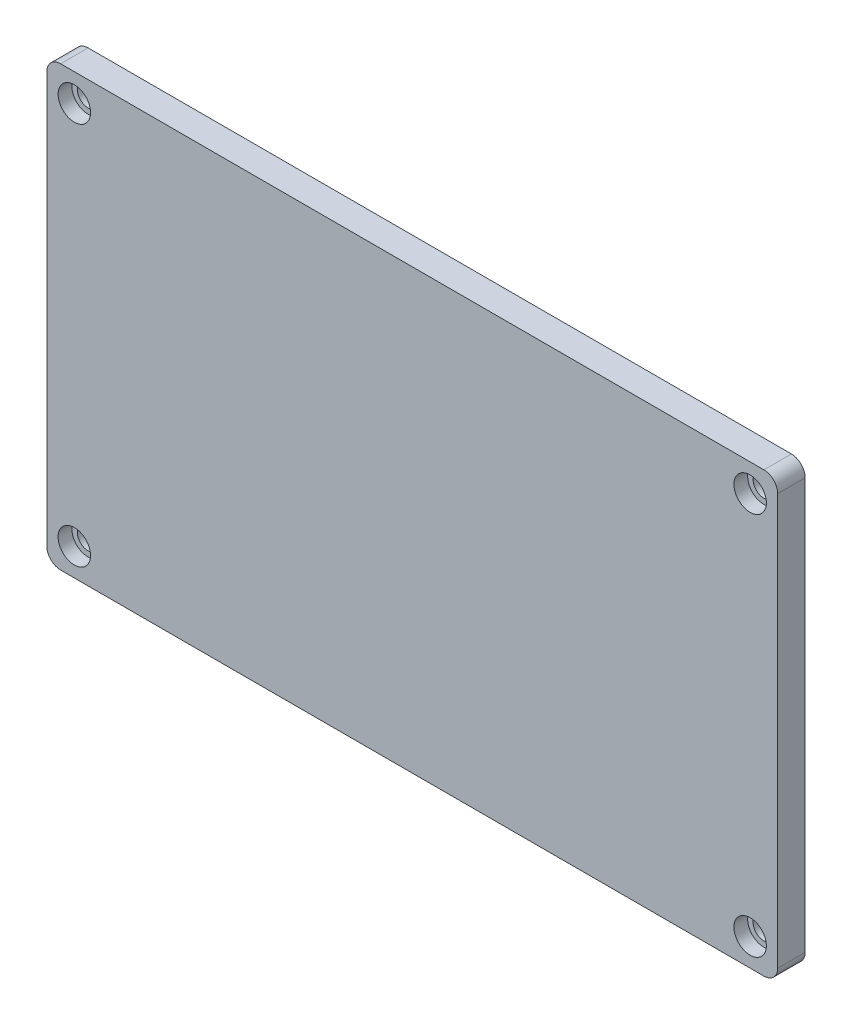
SolidWorks part; units mm, degrees
ref_plane "Front Plane" through (0, 0, 0) normal (0, 0, 1) x (1, 0, 0)
ref_plane "Top Plane" through (0, 0, 0) normal (0, 1, 0) x (1, 0, 0)
ref_plane "Right Plane" through (0, 0, 0) normal (1, 0, 0) x (0, 0, -1)
sketch "Sketch1" plane through (0, 0, 0) normal (0, 0, 1) x (1, 0, 0)
  line L15 (-71.9016, 23.565) -> (-69.4016, 23.565)
  line L16 (-71.9016, 23.565) -> (-71.9016, 20.771)
  line L17 (-71.9016, 20.771) -> (-69.4016, 20.771)
  line L18 (-69.4016, 23.565) -> (-69.4016, 20.771)
  line L26 (-69.3616, -8.232) -> (60.5584, -8.232)
  line L27 (63.0984, -5.692) -> (63.0984, 70.228)
  line L40 (60.5584, 72.768) -> (-69.3616, 72.768)
  line L41 (-71.9016, 70.228) -> (-71.9016, 23.565)
  line L42 (-71.9016, 23.565) -> (-69.4016, 23.565)
  line L43 (-69.4016, 23.565) -> (-69.4016, 55.378)
  line L44 (-60.5116, 64.268) -> (26.7084, 64.268)
  line L45 (35.5984, 55.378) -> (35.5984, 8.158)
  line L46 (26.7084, -0.732) -> (-60.5116, -0.732)
  line L47 (-69.4016, 8.158) -> (-69.4016, 20.771)
  line L48 (-69.4016, 20.771) -> (-71.9016, 20.771)
  line L49 (-71.9016, 20.771) -> (-71.9016, -5.692)
  line L50 (-69.3616, -8.232) -> (60.5584, -8.232)
  line L51 (63.0984, -5.692) -> (63.0984, 70.228)
  line L52 (60.5584, 72.768) -> (-69.3616, 72.768)
  line L53 (-71.9016, 70.228) -> (-71.9016, 23.565)
  line L54 (-71.9016, 23.565) -> (-69.4016, 23.565)
  line L55 (-69.4016, 23.565) -> (-69.4016, 55.378)
  line L56 (-60.5116, 64.268) -> (26.7084, 64.268)
  line L57 (35.5984, 55.378) -> (35.5984, 8.158)
  line L58 (26.7084, -0.732) -> (-60.5116, -0.732)
  line L59 (-69.4016, 8.158) -> (-69.4016, 20.771)
  line L60 (-69.4016, 20.771) -> (-71.9016, 20.771)
  line L61 (-71.9016, 20.771) -> (-71.9016, -5.692)
  circle A2 centre (-66.8216, -3.152) radius 2 construction
  circle A3 centre (-66.8216, 67.688) radius 2 construction
  circle A8 centre (58.0184, -3.152) radius 2 construction
  circle A9 centre (58.0184, 67.688) radius 2 construction
  circle A10 centre (-66.8216, -3.152) radius 2
  circle A11 centre (-66.8216, 67.688) radius 2
  circle A12 centre (58.0184, -3.152) radius 2
  circle A13 centre (58.0184, 67.688) radius 2
  arc A14 (60.5584, -8.232) -> (63.0984, -5.692) centre (60.5584, -5.692) ccw
  arc A15 (63.0984, 70.228) -> (60.5584, 72.768) centre (60.5584, 70.228) ccw
  arc A24 (-69.3616, 72.768) -> (-71.9016, 70.228) centre (-69.3616, 70.228) ccw
  arc A25 (-60.5116, 64.268) -> (-69.4016, 55.378) centre (-60.5116, 55.378) ccw
  arc A26 (35.5984, 55.378) -> (26.7084, 64.268) centre (26.7084, 55.378) ccw
  arc A27 (26.7084, -0.732) -> (35.5984, 8.158) centre (26.7084, 8.158) ccw
  arc A28 (-69.4016, 8.158) -> (-60.5116, -0.732) centre (-60.5116, 8.158) ccw
  arc A29 (-71.9016, -5.692) -> (-69.3616, -8.232) centre (-69.3616, -5.692) ccw
  arc A30 (60.5584, -8.232) -> (63.0984, -5.692) centre (60.5584, -5.692) ccw
  arc A31 (63.0984, 70.228) -> (60.5584, 72.768) centre (60.5584, 70.228) ccw
  arc A32 (-69.3616, 72.768) -> (-71.9016, 70.228) centre (-69.3616, 70.228) ccw
  arc A34 (35.5984, 55.378) -> (26.7084, 64.268) centre (26.7084, 55.378) ccw
  arc A35 (26.7084, -0.732) -> (35.5984, 8.158) centre (26.7084, 8.158) ccw
  arc A36 (-69.4016, 8.158) -> (-60.5116, -0.732) centre (-60.5116, 8.158) ccw
  arc A37 (-71.9016, -5.692) -> (-69.3616, -8.232) centre (-69.3616, -5.692) ccw
  dimension "D1" = 0
extrude "Boss-Extrude1" add sketch "Sketch1" along normal blind 2.54
sketch "Sketch3" plane through (0, 0, 2.54) normal (0, 0, 1) x (1, 0, 0)
  line L5 (-71.9016, 70.228) -> (-71.9016, -5.692)
  line L6 (-69.3616, -8.232) -> (60.5584, -8.232)
  line L7 (63.0984, -5.692) -> (63.0984, 70.228)
  line L12 (60.5584, 72.768) -> (-69.3616, 72.768)
  line L13 (-71.9016, 70.228) -> (-71.9016, -5.692)
  line L16 (-69.3616, -8.232) -> (60.5584, -8.232)
  line L18 (63.0984, -5.692) -> (63.0984, 70.228)
  line L19 (60.5584, 72.768) -> (-69.3616, 72.768)
  circle A17 centre (58.0184, 67.688) radius 3
  circle A18 centre (-66.8216, 67.688) radius 3
  circle A19 centre (-66.8216, 67.688) radius 3
  arc A20 (-69.3616, 72.768) -> (-71.9016, 70.228) centre (-69.3616, 70.228) ccw
  arc A21 (-71.9016, -5.692) -> (-69.3616, -8.232) centre (-69.3616, -5.692) ccw
  arc A26 (60.5584, -8.232) -> (63.0984, -5.692) centre (60.5584, -5.692) ccw
  arc A27 (63.0984, 70.228) -> (60.5584, 72.768) centre (60.5584, 70.228) ccw
  arc A28 (-69.3616, 72.768) -> (-71.9016, 70.228) centre (-69.3616, 70.228) ccw
  arc A29 (-71.9016, -5.692) -> (-69.3616, -8.232) centre (-69.3616, -5.692) ccw
  arc A30 (60.5584, -8.232) -> (63.0984, -5.692) centre (60.5584, -5.692) ccw
  arc A31 (63.0984, 70.228) -> (60.5584, 72.768) centre (60.5584, 70.228) ccw
  circle A32 centre (58.0184, -3.152) radius 3
  circle A33 centre (-66.8216, -3.152) radius 3
  dimension "D1" = 0
  dimension "D2" = 1
extrude "Boss-Extrude2" add sketch "Sketch3" along normal blind 2.54 contours L18 A31 L19 A28 L13 A29 L16 A30 A33 A32 A17 A19
